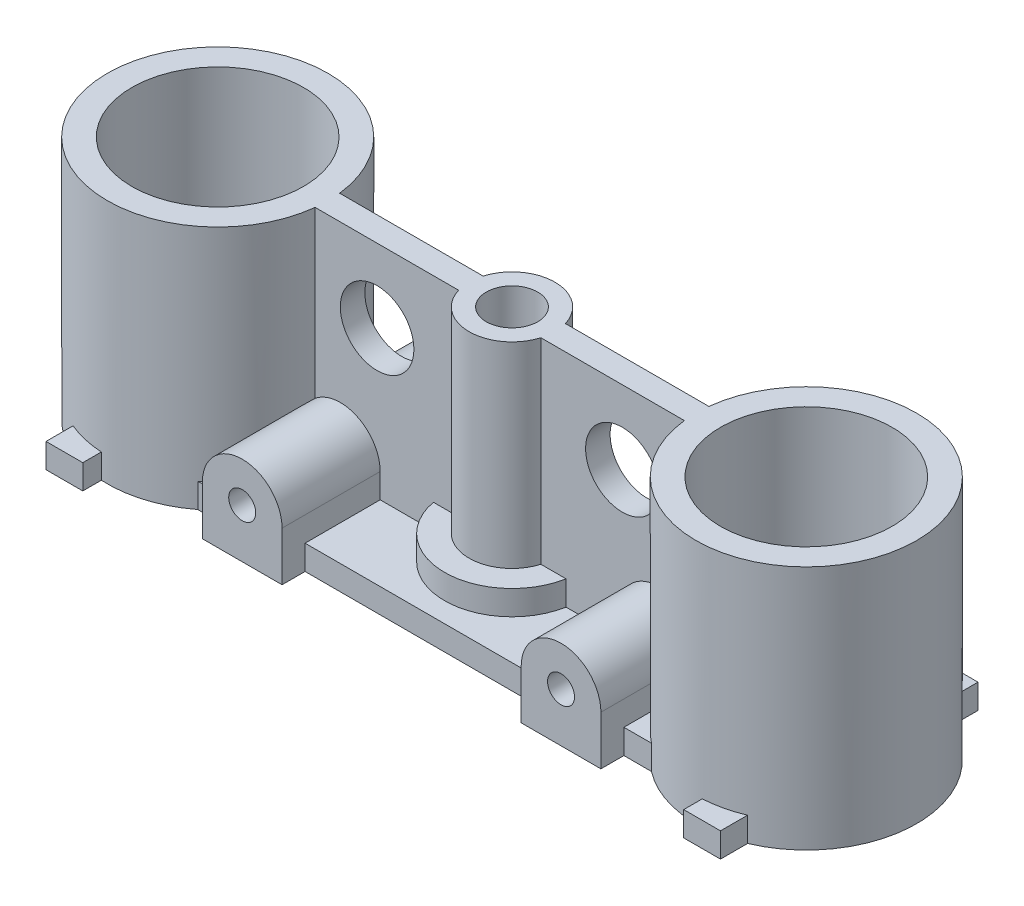
SolidWorks part; units mm, degrees
ref_plane "Front Plane" through (0, 0, 0) normal (0, 0, 1) x (1, 0, 0)
ref_plane "Top Plane" through (0, 0, 0) normal (0, 1, 0) x (1, 0, 0)
ref_plane "Right Plane" through (0, 0, 0) normal (1, 0, 0) x (0, 0, -1)
sketch "Sketch1" plane through (0, 0, 0) normal (0, 1, 0) x (1, 0, 0)
  line L0 (0, 0.5) -> (0, -0.5) construction
  line L1 (12, 0.5) -> (-12, 0.5)
  line L2 (-12, 0.5) -> (-12, -0.5)
  line L3 (-12, -0.5) -> (12, -0.5)
  line L4 (-12, 0) -> (2.4073, 0) construction
  line L5 (12, 0.5) -> (12, -0.5)
  circle A0 centre (0, 0) radius 1.75
  circle A1 centre (0, 0) radius 1.05
  circle A2 centre (-12, 0) radius 2
  circle A3 centre (-12, 0) radius 4.5
  circle A4 centre (12, 0) radius 2
  circle A5 centre (12, 0) radius 4.5
  point P12 (-11.2087, 0)
  dimension "D1" = 2.1
  dimension "D2" = 3.5
  dimension "D5" = 9
  dimension "D6" = 4
  dimension "D3" = 1
  dimension "D4" = 12
extrude "Boss-Extrude1" add sketch "Sketch1" along normal blind 10 contours A5 L1 A4 L3 | L1 A3 L3 A2 | L3 A3 L1 A2 | A5 L3 A4 L1 | L3 A5 L1 A0 | A3 L3 A0 L1 | A1 L3 A0 L1 | A1 L1 A0 L3 | A1 L1 A0 | A1 L3 A0
sketch "Sketch2" plane through (0, 0, 0) normal (0, 1, 0) x (1, 0, 0)
  line L1 (-9.25, 3.562) -> (9.25, 3.562)
  line L2 (-9.25, 3.562) -> (-9.25, -3.562)
  line L3 (-9.25, -3.562) -> (9.25, -3.562)
  line L4 (9.25, 3.562) -> (9.25, -3.562)
  line L5 (-9.25, 3.562) -> (9.25, -3.562) construction
  line L6 (-9.25, -3.562) -> (9.25, 3.562) construction
  line L7 (-13.75, 5.25) -> (13.75, 5.25)
  line L8 (-13.75, 5.25) -> (-13.75, -5.25)
  line L9 (-13.75, -5.25) -> (13.75, -5.25)
  line L10 (13.75, 5.25) -> (13.75, -5.25)
  line L11 (-13.75, 5.25) -> (13.75, -5.25) construction
  line L12 (-13.75, -5.25) -> (13.75, 5.25) construction
  line L13 (-12.25, 5.25) -> (12.25, 5.25)
  line L14 (-12.25, 5.25) -> (-12.25, -5.25)
  line L15 (-12.25, -5.25) -> (12.25, -5.25)
  line L16 (12.25, 5.25) -> (12.25, -5.25)
  line L17 (-12.25, 5.25) -> (12.25, -5.25) construction
  line L18 (-12.25, -5.25) -> (12.25, 5.25) construction
  circle A0 centre (12, 0) radius 2 construction
  circle A1 centre (0, 0) radius 1.05 construction
  circle A2 centre (-12, 0) radius 2 construction
  circle A3 centre (12, 0) radius 2
  circle A4 centre (0, 0) radius 1.05
  circle A5 centre (-12, 0) radius 2
  arc A6 (7.5279, -0.5) -> (7.5279, 0.5) centre (12, 0) ccw construction
  point P2 (9.25, 3.8836)
  point P21 (0, 0)
  point P24 (9.25, 3.562)
  point P28 (0, 0)
  dimension "D1" = 18.5
  dimension "D2" = 10.5
  dimension "D3" = 27.5
  dimension "D4" = 24.5
extrude "Boss-Extrude2" add sketch "Sketch2" along normal blind 1 contours A5 L14 L7 L8 | A5 L8 L9 L14 | A3 L10 L7 L16 | A3 L16 L9 L10 | L4 L1 L2 L3 A4
sketch "Sketch3" plane through (0, 10, 0) normal (0, 1, 0) x (1, 0, 0)
  circle A0 centre (-12, 0) radius 3.5
  circle A1 centre (12, 0) radius 3.5
  dimension "D1" = 7
  dimension "D2" = 7
extrude "Cut-Extrude1" cut sketch "Sketch3" against normal blind 8.5
sketch "Sketch4" plane through (0, 0, 0) normal (0, 0, 1) x (1, 0, 0)
  line L0 (-8.125, 0) -> (-4.875, 0)
  line L1 (-9.25, 0) -> (9.25, 0) construction
  line L2 (-4.875, 0) -> (-4.875, 2)
  line L3 (-8.125, 0) -> (-8.125, 2)
  line L4 (0, 0) -> (0, 13.744) construction
  line L5 (8.125, 0) -> (4.875, 0)
  line L6 (4.875, 0) -> (4.875, 2)
  line L7 (8.125, 0) -> (8.125, 2)
  arc A0 (-8.125, 2) -> (-4.875, 2) centre (-6.5, 2) cw
  arc A1 (8.125, 2) -> (4.875, 2) centre (6.5, 2) ccw
  dimension "D1" = 2
  dimension "D2" = 3.25
  dimension "D3" = 6.5
extrude "Boss-Extrude3" add sketch "Sketch4" along normal mid plane 9
sketch "Sketch5" plane through (0, 0, 0) normal (0, 0, 1) x (1, 0, 0)
  line L115 (12, 0) -> (-12, 0) construction
  circle A0 centre (-5, 7) radius 1.5
  circle A1 centre (5, 7) radius 1.5
  point P7 (0, 0)
  point P8 (6.5, 2)
  point P9 (7.5279, 3.2586)
  point P10 (4.875, 2)
  point P11 (-6.5, 2)
  point P12 (-4.875, 2)
  point P13 (-7.5279, 3.2586)
  point P14 (-8.125, 1)
  point P15 (-8.125, 0)
  point P16 (-4.875, 0)
  point P17 (-4.875, 1)
  point P18 (8.125, 0)
  point P19 (8.125, 1)
  point P20 (4.875, 1)
  point P21 (4.875, 0)
  point P22 (-1.6771, 1)
  point P23 (-4.875, 1)
  point P24 (-7.5279, 10)
  point P25 (-7.5279, 3.2586)
  point P26 (-1.6771, 10)
  point P27 (-1.6771, 1)
  point P28 (1.6771, 10)
  point P29 (1.6771, 1)
  point P30 (7.5279, 10)
  point P31 (7.5279, 3.2586)
  point P32 (7.5279, 10)
  point P33 (7.5279, 3.2586)
  point P34 (1.6771, 10)
  point P35 (1.6771, 1)
  point P36 (-1.6771, 10)
  point P37 (-1.6771, 1)
  point P38 (-7.5279, 10)
  point P39 (-7.5279, 3.2586)
  point P40 (1.05, 10)
  point P41 (-1.05, 10)
  point P42 (-1.6771, 10)
  point P43 (-7.5279, 10)
  point P44 (1.6771, 10)
  point P45 (-1.6771, 10)
  point P46 (7.5279, 10)
  point P47 (1.6771, 10)
  point P48 (16.5, 10)
  point P49 (7.5279, 10)
  point P50 (1.6771, 10)
  point P51 (7.5279, 10)
  point P52 (1.6771, 10)
  point P53 (-1.6771, 10)
  point P54 (-7.5279, 10)
  point P55 (-1.6771, 10)
  point P56 (-7.5279, 10)
  point P57 (-16.5, 10)
  point P58 (10, 0)
  point P59 (14, 0)
  point P60 (-14, 0)
  point P61 (-10, 0)
  point P62 (-1.05, 0)
  point P63 (1.05, 0)
  point P64 (9.25, 0)
  point P65 (12.25, 0)
  point P66 (13.75, 0)
  point P67 (16.5, 0)
  point P68 (9.25, 0)
  point P69 (12.25, 0)
  point P70 (-12.25, 0)
  point P71 (-9.25, 0)
  point P72 (-16.5, 0)
  point P73 (-13.75, 0)
  point P74 (-12.25, 0)
  point P75 (-9.25, 0)
  point P76 (-12.25, 1)
  point P77 (-13.75, 1)
  point P78 (-12.25, 1)
  point P79 (-13.75, 1)
  point P80 (-8.125, 1)
  point P81 (-9.25, 1)
  point P82 (-4.875, 1)
  point P83 (-1.6771, 1)
  point P84 (1.6771, 1)
  point P85 (-1.6771, 1)
  point P86 (1.6771, 1)
  point P87 (4.875, 1)
  point P88 (9.25, 1)
  point P89 (8.125, 1)
  point P90 (-8.125, 1)
  point P91 (-9.25, 1)
  point P92 (9.25, 1)
  point P93 (8.125, 1)
  point P94 (4.875, 1)
  point P95 (1.6771, 1)
  point P96 (1.6771, 1)
  point P97 (-1.6771, 1)
  point P98 (13.75, 1)
  point P99 (12.25, 1)
  point P100 (13.75, 1)
  point P101 (12.25, 1)
  point P102 (-13.75, 1)
  point P103 (-13.75, 0)
  point P104 (-12.25, 1)
  point P105 (-12.25, 0)
  point P106 (13.75, 1)
  point P107 (13.75, 0)
  point P108 (12.25, 1)
  point P109 (12.25, 0)
  point P110 (12.25, 0)
  point P111 (12.25, 1)
  point P112 (13.75, 0)
  point P113 (13.75, 1)
  point P114 (-12.25, 0)
  point P115 (-12.25, 1)
  point P116 (-13.75, 0)
  point P117 (-13.75, 1)
  point P118 (-12.25, 1)
  point P119 (-12.25, 0)
  point P120 (-13.75, 1)
  point P121 (-13.75, 0)
  point P122 (-13.75, 1)
  point P123 (-12.25, 1)
  point P124 (-13.75, 0)
  point P125 (-12.25, 0)
  point P126 (-13.75, 1)
  point P127 (-13.75, 0)
  point P128 (-12.25, 1)
  point P129 (-12.25, 0)
  point P130 (-13.75, 1)
  point P131 (-12.25, 1)
  point P132 (-13.75, 0)
  point P133 (-12.25, 0)
  point P134 (13.75, 1)
  point P135 (13.75, 0)
  point P136 (12.25, 1)
  point P137 (12.25, 0)
  point P138 (12.25, 1)
  point P139 (13.75, 1)
  point P140 (12.25, 0)
  point P141 (13.75, 0)
  point P142 (12.25, 1)
  point P143 (12.25, 0)
  point P144 (13.75, 1)
  point P145 (13.75, 0)
  point P146 (12.25, 1)
  point P147 (13.75, 1)
  point P148 (12.25, 0)
  point P149 (13.75, 0)
  point P150 (9.25, 1)
  point P151 (9.25, 0)
  point P152 (-9.25, 1)
  point P153 (-9.25, 0)
  point P154 (-9.25, 1)
  point P155 (-9.25, 0)
  point P156 (9.25, 1)
  point P157 (9.25, 0)
  point P158 (-9.25, 1)
  point P159 (-8.125, 1)
  point P160 (-4.875, 1)
  point P161 (4.875, 1)
  point P162 (8.125, 1)
  point P163 (9.25, 1)
  point P164 (-9.25, 1)
  point P165 (-8.125, 1)
  point P166 (-4.875, 1)
  point P167 (4.875, 1)
  point P168 (8.125, 1)
  point P169 (9.25, 1)
  point P170 (-9.25, 0)
  point P171 (-8.125, 0)
  point P172 (-4.875, 0)
  point P173 (4.875, 0)
  point P174 (8.125, 0)
  point P175 (9.25, 0)
  point P176 (-9.25, 0)
  point P177 (-8.125, 0)
  point P178 (-4.875, 0)
  point P179 (4.875, 0)
  point P180 (8.125, 0)
  point P181 (9.25, 0)
  point P182 (-10, 1.5)
  point P183 (-14, 1.5)
  point P184 (14, 1.5)
  point P185 (10, 1.5)
  point P186 (-8.5, 1.5)
  point P187 (-15.5, 1.5)
  point P188 (-8.5, 10)
  point P189 (-15.5, 10)
  point P190 (15.5, 10)
  point P191 (8.5, 10)
  point P192 (15.5, 1.5)
  point P193 (8.5, 1.5)
  point P194 (6.5, 2)
  point P195 (8.125, 2)
  point P196 (7.5279, 3.2586)
  point P197 (6.5, 2)
  point P198 (7.5279, 3.2586)
  point P199 (4.875, 2)
  point P200 (6.5, 2)
  point P201 (8.125, 2)
  point P202 (7.5279, 3.2586)
  point P203 (-6.5, 2)
  point P204 (-7.5279, 3.2586)
  point P205 (-8.125, 2)
  point P206 (-6.5, 2)
  point P207 (-4.875, 2)
  point P208 (-7.5279, 3.2586)
  point P209 (-6.5, 2)
  point P210 (-7.5279, 3.2586)
  point P211 (-8.125, 2)
  point P212 (-8.125, 1)
  point P213 (-8.125, 2)
  point P214 (-8.125, 1)
  point P215 (-8.125, 0)
  point P216 (-8.125, 2)
  point P217 (-8.125, 1)
  point P218 (-4.875, 2)
  point P219 (-4.875, 1)
  point P220 (-4.875, 0)
  point P221 (-4.875, 1)
  point P222 (-4.875, 1)
  point P223 (-4.875, 2)
  point P224 (8.125, 1)
  point P225 (8.125, 2)
  point P226 (8.125, 0)
  point P227 (8.125, 1)
  point P228 (8.125, 2)
  point P229 (8.125, 1)
  point P230 (4.875, 1)
  point P231 (4.875, 2)
  point P232 (4.875, 1)
  point P233 (4.875, 0)
  point P234 (4.875, 2)
  point P235 (4.875, 1)
  point P236 (-6.5, 2)
  point P237 (-4.875, 2)
  point P238 (-8.125, 2)
  point P239 (-4.875, 0)
  point P240 (-4.875, 2)
  point P241 (-8.125, 0)
  point P242 (-4.875, 0)
  point P243 (-8.125, 2)
  point P244 (-8.125, 0)
  point P245 (-6.5, 2)
  point P246 (-4.875, 2)
  point P247 (-8.125, 2)
  point P248 (-4.875, 0)
  point P249 (-4.875, 2)
  point P250 (-8.125, 0)
  point P251 (-4.875, 0)
  point P252 (-8.125, 2)
  point P253 (-8.125, 0)
  point P254 (8.125, 0)
  point P255 (8.125, 2)
  point P256 (6.5, 2)
  point P257 (8.125, 2)
  point P258 (4.875, 2)
  point P259 (4.875, 2)
  point P260 (4.875, 0)
  point P261 (4.875, 0)
  point P262 (8.125, 0)
  point P263 (8.125, 0)
  point P264 (8.125, 2)
  point P265 (6.5, 2)
  point P266 (8.125, 2)
  point P267 (4.875, 2)
  point P268 (4.875, 2)
  point P269 (4.875, 0)
  point P270 (4.875, 0)
  point P271 (8.125, 0)
  dimension "D2" = 3
  dimension "D1" = 10
  dimension "D3" = 5
  dimension "D4" = 7
extrude "Cut-Extrude2" cut sketch "Sketch5" against normal mid plane 9
hole_wizard "M1.4x0.3 Tapped Hole1" positions "3DSketch1" profile "Sketch6" tap size "M1.4x0.3" standard "ANSI Metric" end condition through all
sketch3d "3DSketch1"
  line L0 (-6.5, 2, 4.5) -> (-6.5, 2, 0.5) construction
  line L1 (6.5, 2, 4.5) -> (6.5, 2, 0.5) construction
  point P0 (-6.5, 2, 4.5)
  point P4 (6.5, 2, 4.5)
sketch "Sketch6" plane through (-6.5, 2, 4.5) normal (1, 0, 0) x (0, -1, 0)
  line L0 (0, 0) -> (0, 9.75)
  line L1 (0, 9.75) -> (0.55, 9.75)
  line L2 (0.55, 9.75) -> (0.55, 0)
  line L5 (0.55, 0) -> (0, 0)
  line L11 (0, -6.35) -> (0, 107.95) construction
  dimension "Thru Tap Drill Dia." = 1.1
  dimension "Thru Tap Drill Depth" = 9.75
cosmetic thread "Hole Thread1" parameters "D2"=1.4
cosmetic thread "Hole Thread2" parameters "D2"=1.4
sketch "Sketch7" plane through (0, 1, 0) normal (0, 1, 0) x (1, 0, 0)
  circle A0 centre (0, 0) radius 1.75
  circle A1 centre (0, 0) radius 2.75
  dimension "D1" = 5.5
  dimension "D2" = 3.5
extrude "Boss-Extrude4" add sketch "Sketch7" along normal blind 1
sketch "Sketch8" plane through (0, 0, 0) normal (0, -1, 0) x (1, 0, 0)
  circle A0 centre (0, 0) radius 2
  dimension "D1" = 4
extrude "Cut-Extrude3" cut sketch "Sketch8" against normal blind 1
